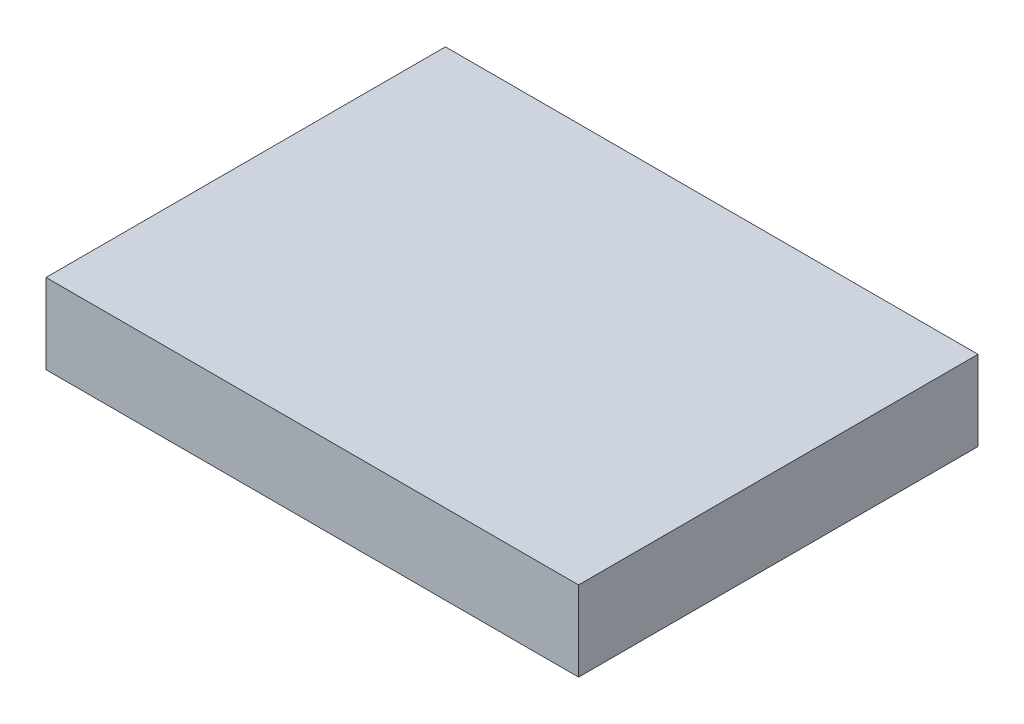
SolidWorks part; units mm, degrees
ref_plane "Front Plane" through (0, 0, 0) normal (0, 0, 1) x (1, 0, 0)
ref_plane "Top Plane" through (0, 0, 0) normal (0, 1, 0) x (1, 0, 0)
ref_plane "Right Plane" through (0, 0, 0) normal (1, 0, 0) x (0, 0, -1)
other "Center of Mass"
sketch "Sketch1" plane through (0, 0, 0) normal (0, 1, 0) x (1, 0, 0)
  line L1 (10, 7.5) -> (-10, 7.5)
  line L2 (10, 7.5) -> (10, -7.5)
  line L3 (10, -7.5) -> (-10, -7.5)
  line L4 (-10, 7.5) -> (-10, -7.5)
  line L5 (10, 7.5) -> (-10, -7.5) construction
  line L6 (10, -7.5) -> (-10, 7.5) construction
  point P0 (0, 0)
  dimension "D1" = 20
  dimension "D2" = 15
extrude "Boss-Extrude1" add sketch "Sketch1" along normal blind 3
equation "\"alto\"= 0.3"
equation "\"D1@Boss-Extrude1\"=\"alto\""
equation "\"largo\"=2"
equation "\"D1@Sketch1\"=\"largo\""
equation "\"ancho\"=1.5"
equation "\"D2@Sketch1\"=\"ancho\""
